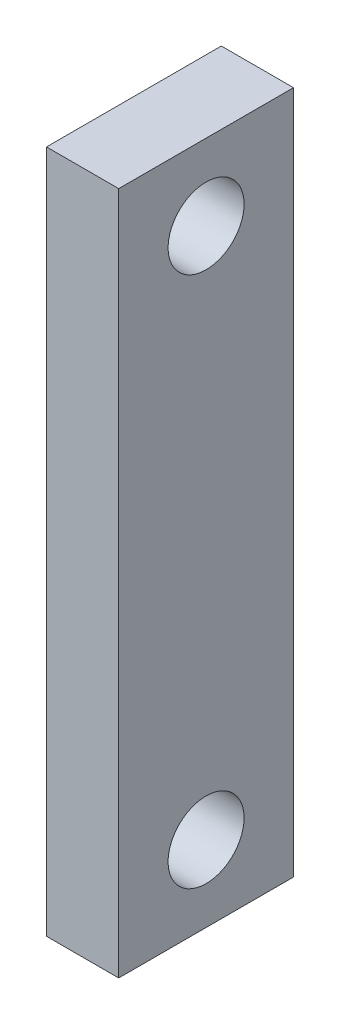
SolidWorks part; units mm, degrees
material "PE High Density"
ref_plane "Front Plane" through (0, 0, 0) normal (0, 0, 1) x (1, 0, 0)
ref_plane "Top Plane" through (0, 0, 0) normal (0, 1, 0) x (1, 0, 0)
ref_plane "Right Plane" through (0, 0, 0) normal (1, 0, 0) x (0, 0, -1)
sketch "Sketch1" plane through (0, 0, 0) normal (0, 1, 0) x (1, 0, 0)
  line L1 (-47.5, 115) -> (47.5, 115)
  line L2 (-47.5, 115) -> (-47.5, -115)
  line L3 (-47.5, -115) -> (47.5, -115)
  line L4 (47.5, 115) -> (47.5, -115)
  line L5 (-47.5, 115) -> (47.5, -115) construction
  line L6 (-47.5, -115) -> (47.5, 115) construction
  point P0 (0, 0)
  dimension "D1" = 95
  dimension "D2" = 230
extrude "Boss-Extrude1" add sketch "Sketch1" along normal blind 899.5733
sketch "Sketch2" plane through (47.5, 0, 0) normal (1, 0, 0) x (0, 0, -1)
  line L0 (-115, 899.5733) -> (115, 899.5733) construction
  circle A0 centre (0, 799.5733) radius 50
  dimension "D1" = 100
  dimension "D2" = 100
extrude "Cut-Extrude1" cut sketch "Sketch2" against normal blind 1200
sketch "Sketch5" plane through (47.5, 0, 0) normal (1, 0, 0) x (0, 0, -1)
  line L0 (-115, 0) -> (115, 0) construction
  circle A0 centre (0, 100) radius 50
  dimension "D1" = 100
  dimension "D2" = 100
extrude "Cut-Extrude4" cut sketch "Sketch5" against normal blind 226
scale "Scale1" scale about centroid uniform scaling yes scale factor 0.75
